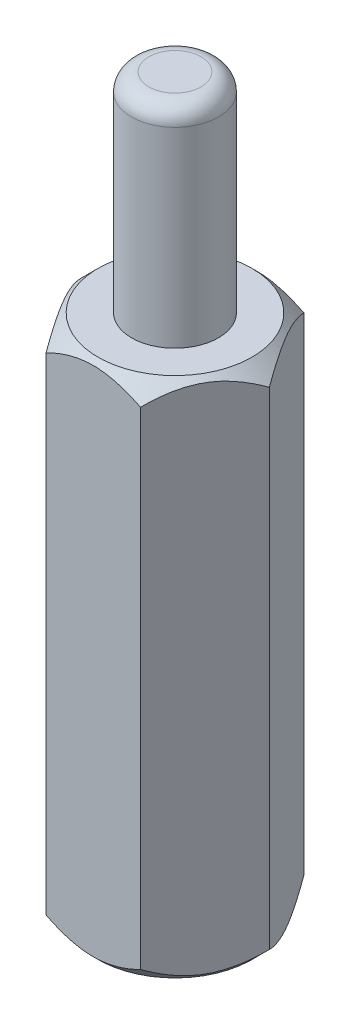
SolidWorks part; units mm, degrees
ref_plane "前视基准面" through (0, 0, 0) normal (0, 0, 1) x (1, 0, 0)
ref_plane "上视基准面" through (0, 0, 0) normal (0, 1, 0) x (1, 0, 0)
ref_plane "右视基准面" through (0, 0, 0) normal (1, 0, 0) x (0, 0, -1)
other "Configuration Table"
sketch "草图1" plane through (0, 0, 0) normal (0, 1, 0) x (1, 0, 0)
  line L1 (2.7135, 0) -> (1.3568, 2.35)
  line L2 (1.3568, 2.35) -> (-1.3568, 2.35)
  line L3 (-1.3568, 2.35) -> (-2.7135, 0)
  line L4 (-2.7135, 0) -> (-1.3568, -2.35)
  line L5 (-1.3568, -2.35) -> (1.3568, -2.35)
  line L6 (1.3568, -2.35) -> (2.7135, 0)
  circle A0 centre (0, 0) radius 2.35 construction
  dimension "D1" = 4.7
extrude "凸台-拉伸1" add sketch "草图1" along normal blind 15
sketch "草图2" plane through (0, 0, 0) normal (0, -1, 0) x (1, 0, 0)
  circle A0 centre (0, 0) radius 1.25
  dimension "D1" = 2.5
extrude "切除-拉伸1" cut sketch "草图2" against normal blind 10
sketch "草图4" plane through (0, 15, 0) normal (0, 1, 0) x (1, 0, 0)
  line L6 (1.3568, -2.35) -> (2.7135, 0)
  line L7 (2.7135, 0) -> (1.3568, 2.35)
  line L8 (1.3568, 2.35) -> (-1.3568, 2.35)
  line L9 (-1.3568, 2.35) -> (-2.7135, 0)
  line L10 (-2.7135, 0) -> (-1.3568, -2.35)
  line L11 (-1.3568, -2.35) -> (1.3568, -2.35)
  line L12 (1.3568, -2.35) -> (2.7135, 0)
  line L13 (2.7135, 0) -> (1.3568, 2.35)
  line L14 (1.3568, 2.35) -> (-1.3568, 2.35)
  line L15 (-1.3568, 2.35) -> (-2.7135, 0)
  line L16 (-2.7135, 0) -> (-1.3568, -2.35)
  line L17 (-1.3568, -2.35) -> (1.3568, -2.35)
  circle A1 centre (0, 0) radius 1.25
  circle A2 centre (0, 0) radius 1.25
  dimension "D1" = 0
  dimension "D2" = 0
extrude "凸台-拉伸2" add sketch "草图4" along normal blind 6 separate body contours A2
fillet "圆角1" radius 0.5 1 edges at (0, 21, 1.25)
sketch "草图7" plane through (0, 0, 0) normal (0, 0, 1) x (1, 0, 0)
  line L0 (-2.7135, 15) -> (-2.7135, 14.5)
  line L1 (-2.7135, 15) -> (-2.7135, 0) construction
  line L2 (-2.7135, 14.5) -> (-2.2135, 15)
  line L3 (-2.7135, 15) -> (-1.3568, 15) construction
  line L4 (-2.2135, 15) -> (-2.7135, 15)
  line L5 (0, 0) -> (1.4452, 0.3873)
  line L6 (0, 0) -> (0, 8.786) construction
  dimension "D1" = 0.5
  dimension "D2" = 0.5
revolve "切除-旋转4" cut sketch "草图7" angle 360 about L6
ref_plane "基准面1" through (0, 7.5, 0) normal (0, -1, 0) x (-1, 0, 0)
mirror "镜向1" about plane through (0, 7.5, 0) normal (0, -1, 0) of "切除-旋转4"
